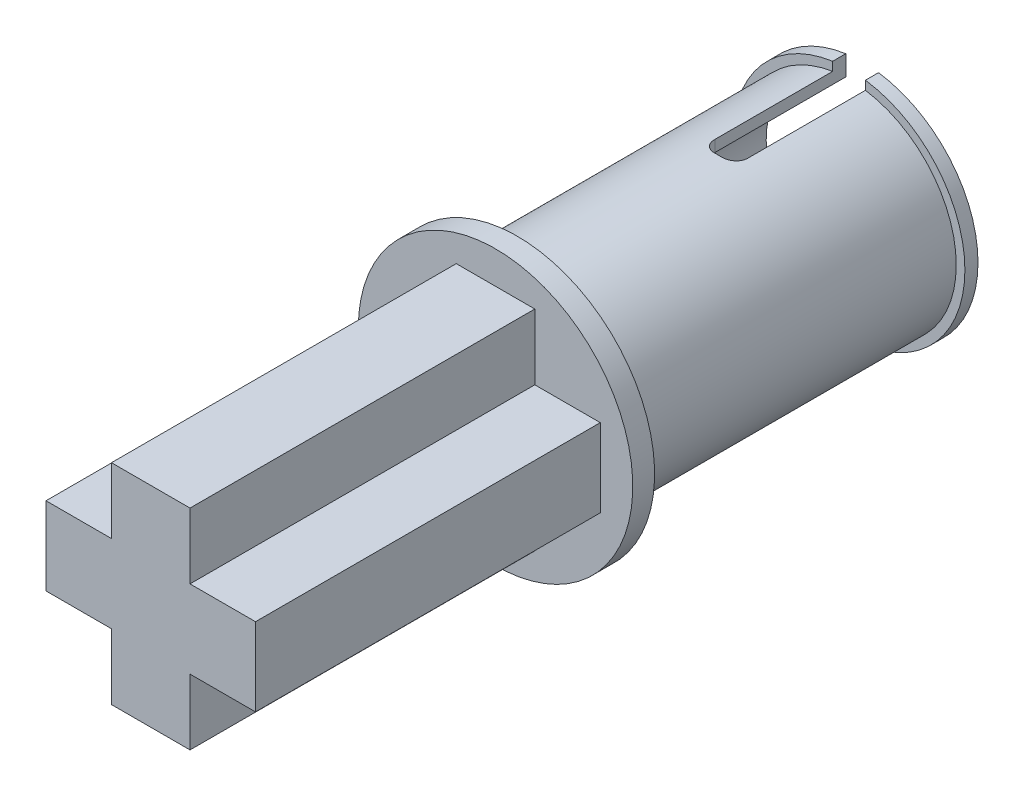
SolidWorks part; units mm, degrees
ref_plane "Front Plane" through (0, 0, 0) normal (0, 0, 1) x (1, 0, 0)
ref_plane "Top Plane" through (0, 0, 0) normal (0, 1, 0) x (1, 0, 0)
ref_plane "Right Plane" through (0, 0, 0) normal (1, 0, 0) x (0, 0, -1)
sketch "Sketch1" plane through (0, 0, 0) normal (0, 0, 1) x (1, 0, 0)
  line L0 (-2.4, 0) -> (2.4, 0)
  line L1 (-2.4, 0.895) -> (-2.4, -0.895)
  line L2 (-2.4, 0.895) -> (-0.9, 0.895)
  line L3 (0, 2.4) -> (0, -2.4)
  line L4 (-0.9, 0.895) -> (-0.9, 2.4)
  line L5 (-0.9, 2.4) -> (0.9, 2.4)
  line L6 (0.9, 0.895) -> (0.9, 2.4)
  line L7 (2.4, 0.895) -> (0.9, 0.895)
  line L8 (2.4, 0.895) -> (2.4, -0.895)
  line L9 (2.4, -0.895) -> (0.9, -0.895)
  line L10 (0.9, -0.895) -> (0.9, -2.4)
  line L11 (-0.9, -2.4) -> (0.9, -2.4)
  line L12 (-0.9, -0.895) -> (-0.9, -2.4)
  line L13 (-2.4, -0.895) -> (-0.9, -0.895)
  point P4 (0, 0)
  point P8 (-2.4, 0)
  point P12 (0, 0)
  dimension "D1" = 4.8
  dimension "D2" = 1.79
  dimension "D3" = 1.5
  dimension "D4" = 4.8
extrude "Boss-Extrude1" add sketch "Sketch1" along normal blind 7.9 contours L5 L4 L2 L1 L0 L3 | L1 L13 L12 L11 L3 L0 | L8 L7 L6 L5 L3 L0 | L3 L11 L10 L9 L8 L0
sketch "Sketch2" plane through (0, 0, 0) normal (0, 0, -1) x (-1, 0, 0)
  circle A0 centre (0, 0) radius 3.1445
extrude "Boss-Extrude3" add sketch "Sketch2" along normal blind 0.5 contours A0
sketch "Sketch3" plane through (0, 0, -0.5) normal (0, 0, -1) x (-1, 0, 0)
  circle A0 centre (0, 0) radius 2.4559
extrude "Boss-Extrude4" add sketch "Sketch3" along normal blind 7.9
sketch "Sketch4" plane through (0, 0, -8.4) normal (0, 0, -1) x (-1, 0, 0)
  circle A0 centre (0, 0) radius 2.6546
extrude "Boss-Extrude5" add sketch "Sketch4" against normal blind 0.3
sketch "Sketch5" plane through (0, 0, -8.4) normal (0, 0, -1) x (-1, 0, 0)
  circle A0 centre (0, 0) radius 2.1986
extrude "Cut-Extrude1" cut sketch "Sketch5" against normal up to surface (7.9 mm away) up to face at (-2.4559, 0, -0.5)
sketch "Sketch6" plane through (0, 0, -8.4) normal (0, 0, -1) x (-1, 0, 0)
  line L0 (0, 0) -> (2.6546, 0) construction
  line L1 (0, 0) -> (0, 2.6546) construction
  line L2 (0.3755, 2.6546) -> (0.3755, 2.1663)
  line L3 (0.3755, 2.6546) -> (-0.3755, 2.6546)
  line L4 (0, 2.6546) -> (0, 2.1663)
  line L5 (0.3755, 2.1663) -> (-0.3755, 2.1663)
  line L6 (-0.3755, 2.6546) -> (-0.3755, 2.1663)
  line L7 (0.3755, -2.6546) -> (0.3755, -2.1663)
  line L8 (0.3755, -2.6546) -> (-0.3755, -2.6546)
  line L9 (-0.3755, -2.6546) -> (-0.3755, -2.1663)
  line L10 (0.3755, -2.1663) -> (-0.3755, -2.1663)
  circle A0 centre (0, 0) radius 2.6546 construction
  circle A1 centre (0, 0) radius 2.1986 construction
  circle M8 centre (0, 0) radius 2.1986
  circle M9 centre (0, 0) radius 2.6546
extrude "Cut-Extrude2" cut sketch "Sketch6" against normal blind 3.3 contours L4 L2 M9 M8 | L6 L4 M9 M8 | L9 L7 M9 M8
fillet "Fillet1" radius 0.3 4 edges at (-0.3755, -2.2967, -5.1) (0.3755, -2.2967, -5.1) (-0.3755, 2.2967, -5.1) (0.3755, 2.2967, -5.1)
